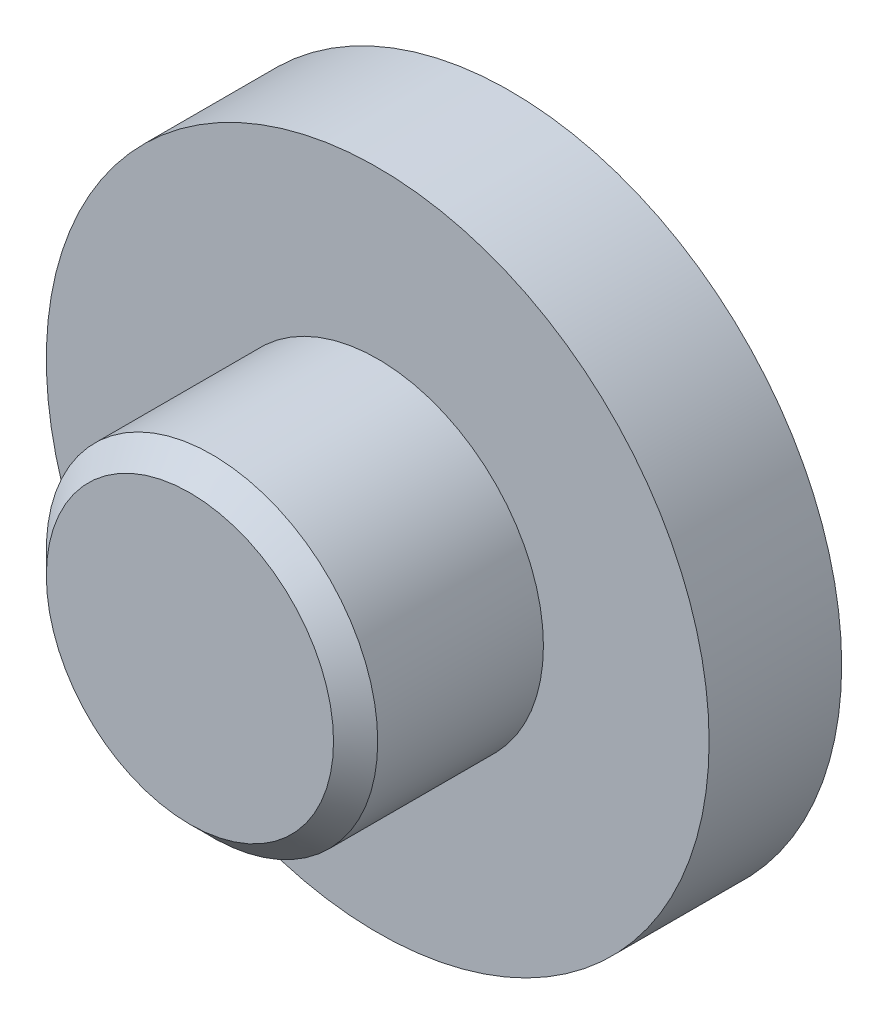
SolidWorks part; units mm, degrees
ref_plane "Front Plane" through (0, 0, 0) normal (0, 0, 1) x (1, 0, 0)
ref_plane "Top Plane" through (0, 0, 0) normal (0, 1, 0) x (1, 0, 0)
ref_plane "Right Plane" through (0, 0, 0) normal (1, 0, 0) x (0, 0, -1)
sketch "Sketch1" plane through (0, 0, 0) normal (0, 0, 1) x (1, 0, 0)
  circle A0 centre (0, 0) radius 30
  point P2 (0, 0)
  point P3 (0, 0)
extrude "Boss-Extrude3" add sketch "Sketch1" along normal blind 12 contours A0
sketch "Sketch3" plane through (0, 0, 12) normal (0, 0, 1) x (1, 0, 0)
  circle A0 centre (0, 0) radius 15
  point P2 (0, 0)
  point P3 (0, 0)
extrude "Boss-Extrude4" add sketch "Sketch3" along normal blind 17 contours A0
chamfer "Chamfer1" distance 2 angle 45 1 edges at (15, 0, 29)
